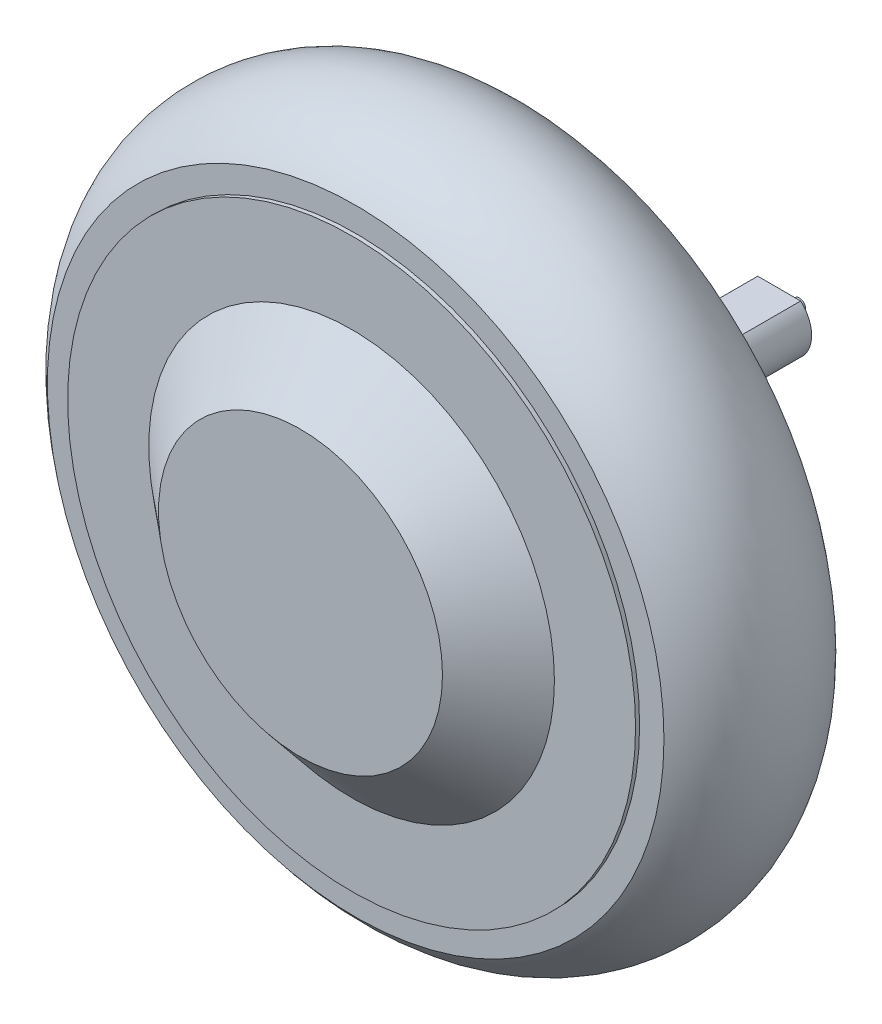
SolidWorks part; units mm, degrees
ref_plane "前视基准面" through (0, 0, 0) normal (0, 0, 1) x (1, 0, 0)
ref_plane "上视基准面" through (0, 0, 0) normal (0, 1, 0) x (1, 0, 0)
ref_plane "右视基准面" through (0, 0, 0) normal (1, 0, 0) x (0, 0, -1)
sketch "草图1" plane through (0, 0, 0) normal (1, 0, 0) x (0, 0, -1)
  line L0 (0, 0) -> (154966.3609, 0) construction
  line L1 (-34.6, 0) -> (-34.6, 35)
  line L2 (-34.6, 35) -> (-22, 50)
  line L3 (0, 0) -> (0, -154966.3609) construction
  line L4 (-22, 50) -> (-22, 70)
  line L5 (-22, 70) -> (-21, 70)
  line L6 (-21, 70) -> (-21, 76)
  line L7 (-1.7245, 86.5) -> (49998.2755, 86.5) construction
  line L8 (21, 70) -> (21, 76)
  line L9 (22, 70) -> (21, 70)
  line L10 (22, 50) -> (22, 70)
  line L11 (34.6, 35) -> (22, 50)
  line L12 (34.6, 25) -> (34.6, 35)
  line L13 (34.6, 25) -> (40.4, 19.2)
  line L14 (40.4, 19.2) -> (40.4, 12)
  line L15 (40.4, 12) -> (45.4, 12)
  line L16 (45.4, 12) -> (45.4, 14)
  line L17 (45.4, 14) -> (48.4, 14)
  line L18 (48.4, 14) -> (48.4, 16)
  line L19 (48.4, 16) -> (50.4, 16)
  line L20 (50.4, 16) -> (50.4, 8)
  line L21 (50.4, 8) -> (83.4, 8)
  line L22 (83.4, 1.5) -> (83.4, 8)
  line L23 (83.4, 1.5) -> (88.4, 1.5)
  line L24 (88.4, 1.5) -> (88.4, 0)
  line L25 (-34.6, 0) -> (88.4, 0)
  arc A0 (-21, 76) -> (21, 76) centre (0, 60.25) cw
  point P24 (34.6, 18.0981)
  point P34 (34.6, 27.8475)
  dimension "D4" = 86.5
  dimension "D9" = 43
  dimension "D1" = 34.6
  dimension "D2" = 44
  dimension "D3" = 1
  dimension "D5" = 50
  dimension "D6" = 35
  dimension "D7" = 6
  dimension "D8" = 20
  dimension "D10" = 5
  dimension "D11" = 16
  dimension "D12" = 24
  dimension "D13" = 14
  dimension "D14" = 16
  dimension "D15" = 5.8
  dimension "D16" = 45
  dimension "D17" = 25
  dimension "D18" = 3
  dimension "D19" = 5
  dimension "D20" = 2
  dimension "D21" = 3
revolve "旋转1" add sketch "草图1" angle 360 about L0
sketch "草图2" plane through (0, 0, -83.4) normal (0, 0, -1) x (-1, 0, 0)
  line L0 (-5.2915, 6) -> (5.2915, 6)
  line L1 (-5.2915, -6) -> (5.2915, -6)
  circle A0 centre (0, 0) radius 8 construction
  arc A1 (5.2915, 6) -> (-5.2915, 6) centre (0, 0) ccw
  arc A2 (-5.2915, -6) -> (5.2915, -6) centre (0, 0) ccw
  dimension "D1" = 12
  dimension "D2" = 6
extrude "切除-拉伸1" cut sketch "草图2" against normal up to surface (33 mm away) and the other way through all up to face at (16, 0, -50.4)
